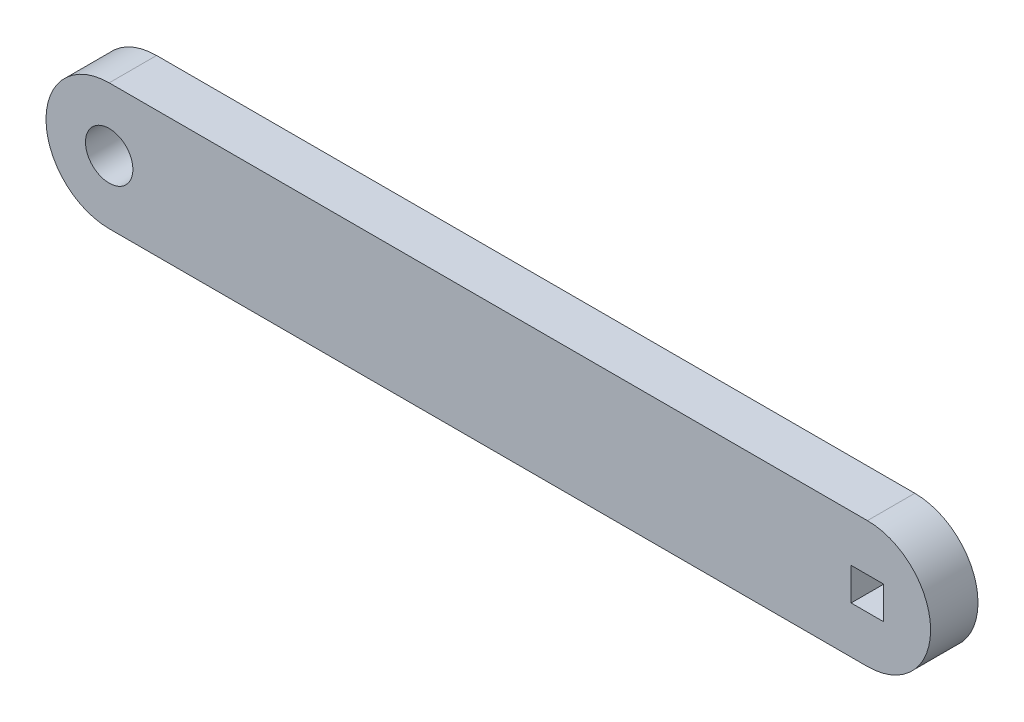
SolidWorks part; units mm, degrees
ref_plane "Front Plane" through (0, 0, 0) normal (0, 0, 1) x (1, 0, 0)
ref_plane "Top Plane" through (0, 0, 0) normal (0, 1, 0) x (1, 0, 0)
ref_plane "Right Plane" through (0, 0, 0) normal (1, 0, 0) x (0, 0, -1)
sketch "Sketch1" plane through (0, 0, 0) normal (0, 0, 1) x (1, 0, 0)
  line L0 (0, 0) -> (76.2, 0) construction
  line L1 (0, 6.35) -> (76.2, 6.35)
  line L2 (0, -6.35) -> (76.2, -6.35)
  line L4 (77.8383, -1.6383) -> (74.5617, -1.6383)
  line L5 (77.8383, -1.6383) -> (77.8383, 1.6383)
  line L6 (77.8383, 1.6383) -> (74.5617, 1.6383)
  line L7 (74.5617, -1.6383) -> (74.5617, 1.6383)
  line L8 (77.8383, -1.6383) -> (74.5617, 1.6383) construction
  line L9 (77.8383, 1.6383) -> (74.5617, -1.6383) construction
  arc A0 (0, 6.35) -> (0, -6.35) centre (0, 0) ccw
  arc A1 (76.2, -6.35) -> (76.2, 6.35) centre (76.2, 0) ccw
  circle A2 centre (0, 0) radius 2.3813
  point P3 (38.1, 0)
  point P10 (76.2, 0)
  dimension "D3" = 4.7625
  dimension "D4" = 3.2766
  dimension "D1" = 76.2
  dimension "D2" = 12.7
extrude "Boss-Extrude1" add sketch "Sketch1" along normal blind 4.7625
